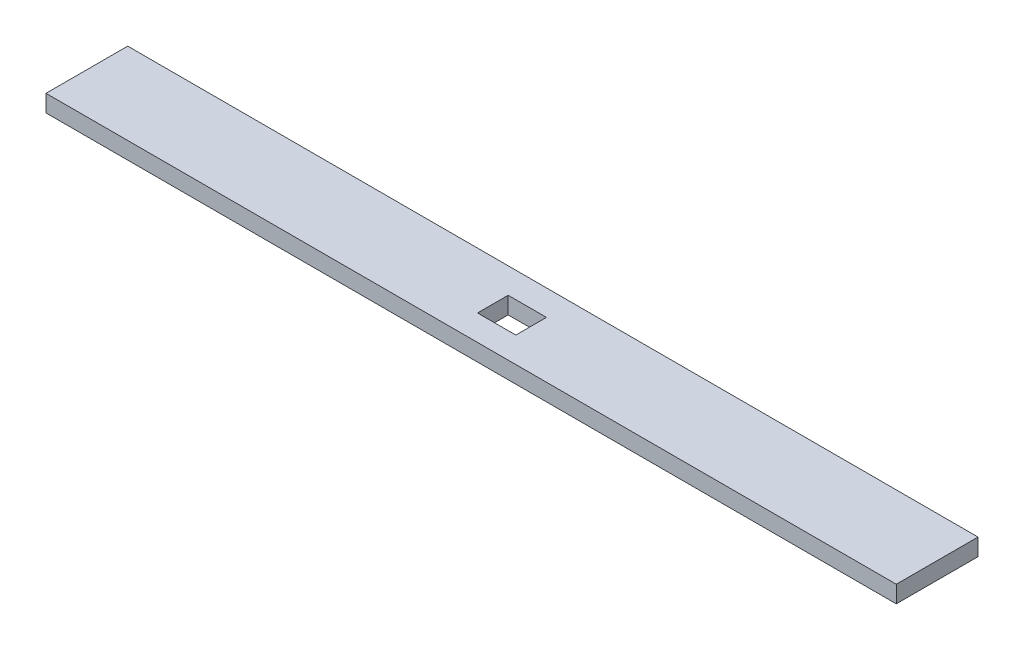
SolidWorks part; units mm, degrees
ref_plane "Front Plane" through (0, 0, 0) normal (0, 0, 1) x (1, 0, 0)
ref_plane "Top Plane" through (0, 0, 0) normal (0, 1, 0) x (1, 0, 0)
ref_plane "Right Plane" through (0, 0, 0) normal (1, 0, 0) x (0, 0, -1)
sketch "Sketch1" plane through (0, 0, 0) normal (1, 0, 0) x (0, 0, -1)
  line L1 (0, 0) -> (48, 0)
  line L2 (0, 0) -> (0, 10)
  line L3 (0, 10) -> (48, 10)
  line L4 (48, 0) -> (48, 10)
  dimension "D1" = 48
  dimension "D2" = 10
extrude "Boss-Extrude1" add sketch "Sketch1" along normal blind 499.5
ref_plane "Plane1" through (0, 0, -24) normal (0, 0, 1) x (1, 0, 0)
ref_plane "Plane2" through (249.75, 0, 0) normal (-1, 0, 0) x (0, 0, 1)
sketch "Sketch2" plane through (0, 10, 0) normal (0, 1, 0) x (1, 0, 0)
  line L0 (499.5, 24) -> (479.9185, 24) construction
  line L1 (261, 15) -> (238.5, 15)
  line L2 (261, 15) -> (261, 33)
  line L3 (261, 33) -> (238.5, 33)
  line L4 (238.5, 15) -> (238.5, 33)
  line L5 (499.5, 48) -> (499.5, 0) construction
  line L6 (499.5, 0) -> (0, 0) construction
  point P8 (249.75, 15)
  point P11 (249.75, 0)
  dimension "D1" = 18
  dimension "D2" = 22.5
extrude "Cut-Extrude1" cut sketch "Sketch2" against normal through all
pattern_linear "LPattern1" [suppressed] count 2 spacing 120
